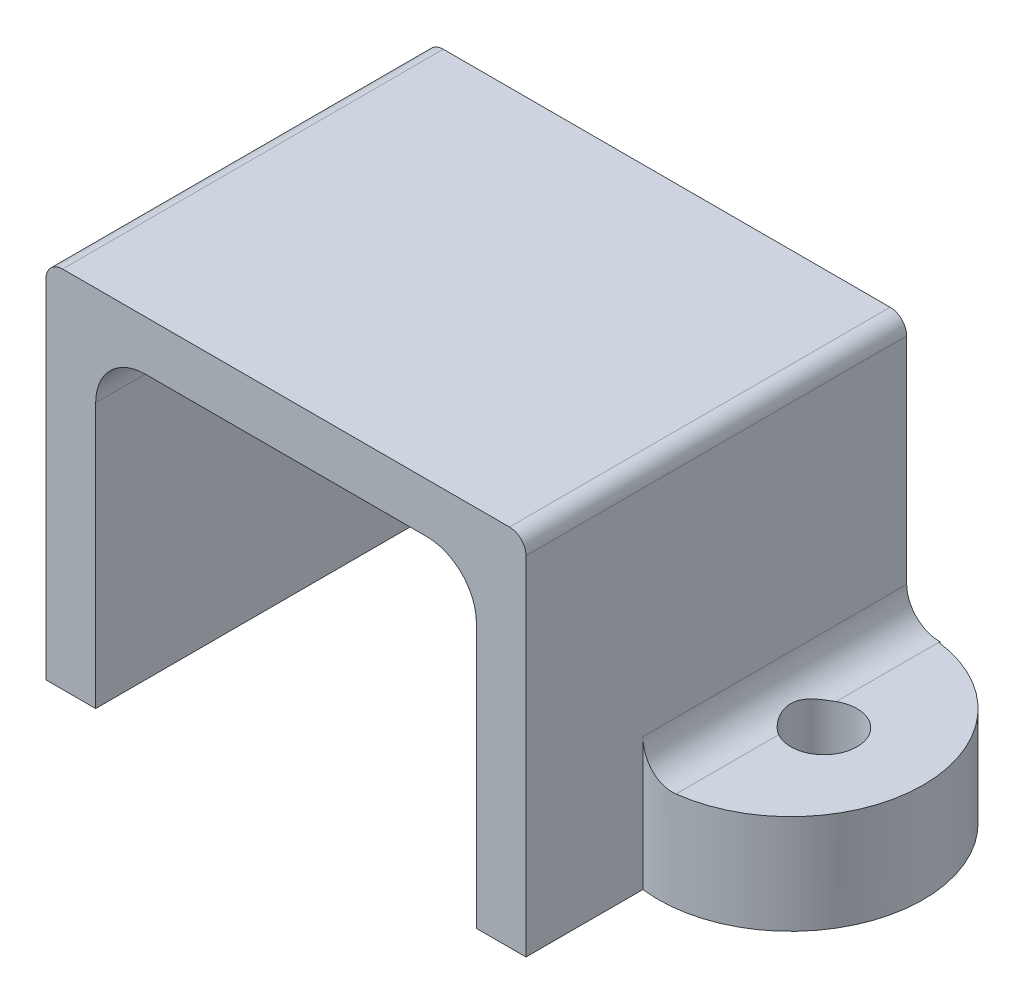
SolidWorks part; units mm, degrees
material "ABS"
ref_plane "Alzado" through (0, 0, 0) normal (0, 0, 1) x (1, 0, 0)
ref_plane "Planta" through (0, 0, 0) normal (0, 1, 0) x (1, 0, 0)
ref_plane "Vista lateral" through (0, 0, 0) normal (1, 0, 0) x (0, 0, -1)
sketch "Croquis1" plane through (0, 0, 0) normal (0, 0, 1) x (1, 0, 0)
  line L0 (7.25, 0) -> (0, 0)
  line L1 (7.25, 0) -> (7.25, -7)
  line L2 (5.75, -11) -> (11.75, -11)
  line L3 (11.75, -11) -> (11.75, -8)
  line L4 (11.75, -8) -> (8.25, -8)
  line L5 (0, 0) -> (0, -1.5)
  line L6 (0, -1.5) -> (4.25, -1.5)
  line L7 (5.75, -3) -> (5.75, -11)
  arc A0 (4.25, -1.5) -> (5.75, -3) centre (4.25, -3) cw
  arc A1 (8.25, -8) -> (7.25, -7) centre (8.25, -7) cw
  point P14 (2.125, -1.5)
  dimension "D6" = 1.5
  dimension "D7" = 1
  dimension "D1" = 3
  dimension "D2" = 7.25
  dimension "D3" = 11
  dimension "D4" = 6
  dimension "D5" = 1.5
  dimension "D8" = 1.5
extrude "Saliente-Extruir1" add sketch "Croquis1" along normal blind 11.5
mirror "Simetría1" about plane through (0, 0, 11.5) normal (1, 0, 0) of "Saliente-Extruir1"
fillet "Redondeo1" radius 0.5 2 edges at (-7.25, 0, 5.75) (7.25, 0, 5.75)
sketch "Croquis3" plane through (0, -8, 0) normal (0, 1, 0) x (1, 0, 0)
  line L0 (11.75, -11.5) -> (8.25, -11.5) construction
  line L1 (7.75, 0) -> (7.25, 0)
  line L6 (11.75, -11.5) -> (11.75, 0) construction
  line L7 (7.75, 0) -> (11.75, 0)
  line L8 (11.75, 0) -> (11.75, -11.5)
  line L9 (11.75, -11.5) -> (7.25, -11.5)
  line L10 (7.25, -11.5) -> (7.25, -7.9686)
  line L11 (7.25, -11.5) -> (7.25, 0) construction
  arc A0 (7.25, -7.9686) -> (7.75, 0) centre (7.75, -4) ccw
  line M2 (11.75, 0) -> (8.25, 0)
  line M3 (8.25, 0) -> (8.25, -11.5)
  line M4 (8.25, -11.5) -> (11.75, -11.5)
  line M5 (11.75, -11.5) -> (11.75, 0)
  dimension "D1" = 8
  dimension "D2" = 7.5
extrude "Cortar-Extruir1" cut sketch "Croquis3" against normal through all both and the other way through all contours A0 L10 L9 M3 | A0 M3 M4 M5 | A0 L8 M2 M3
mirror "Simetría2" about plane through (0, 0, 0) normal (1, 0, 0) of "Cortar-Extruir1"
sketch "Croquis4" plane through (0, -8, 0) normal (0, 1, 0) x (1, 0, 0)
  line L0 (8.25, -7.9686) -> (8.25, -0.0314) construction
  line L3 (7.25, -7.9686) -> (7.25, 0) construction
  line L4 (0, 0) -> (0, -12.7496) construction
  circle A0 centre (8.75, -4) radius 1
  circle A3 centre (-8.75, -4) radius 1
  point P3 (8.25, -4)
  dimension "D2" = 2
  dimension "D1" = 1.5
extrude "Cortar-Extruir2" cut sketch "Croquis4" against normal through all both and the other way through all
